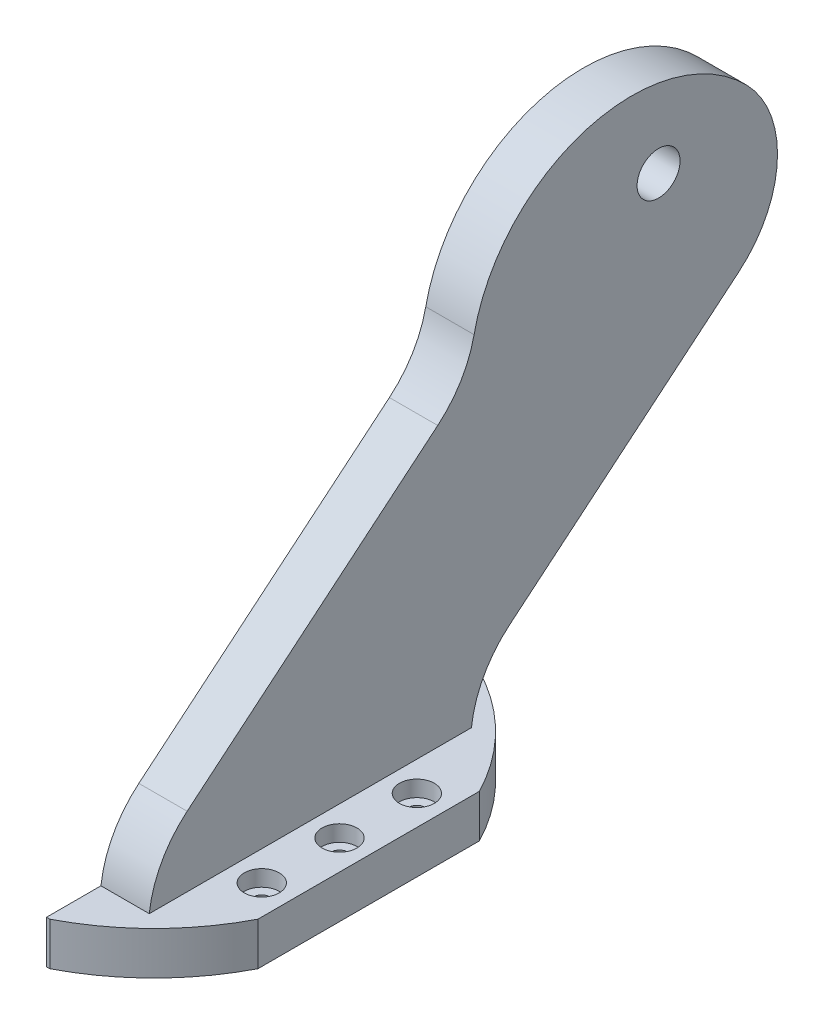
SolidWorks part; units mm, degrees
ref_plane "Alzado" through (0, 0, 0) normal (0, 0, 1) x (1, 0, 0)
ref_plane "Planta" through (0, 0, 0) normal (0, 1, 0) x (1, 0, 0)
ref_plane "Vista lateral" through (0, 0, 0) normal (1, 0, 0) x (0, 0, -1)
sketch "Croquis1" plane through (0, 0, 0) normal (0, 1, 0) x (1, 0, 0)
  line L0 (0, 0) -> (0, 40)
  line L1 (0, 40) -> (20, 40)
  line L2 (20, 40) -> (20, -40)
  line L3 (20, -40) -> (0, -40)
  line L4 (0, -40) -> (0, 0)
extrude "Saliente-Extruir2" add sketch "Croquis1" along normal blind 8
sketch "Croquis3" plane through (0, 8, 0) normal (0, 1, 0) x (1, 0, 0)
  line L0 (20, 0) -> (-20, 0) construction
  line L1 (20, -40) -> (20, 40) construction
  line L3 (0, 40) -> (20, 40)
  line L4 (0, 40) -> (0, -40)
  line L5 (0, -40) -> (20, -40)
  line L6 (20, 40) -> (20, -40)
  circle A0 centre (-20, 0) radius 45
  line M9 (20, -40) -> (20, 40)
  line M10 (20, 40) -> (0, 40)
extrude "Cortar-Extruir1" cut sketch "Croquis3" against normal blind 8 contours A0 M9 M10 | A0 L5 M9
sketch "Croquis4" plane through (0, 0, 0) normal (1, 0, 0) x (0, 0, -1)
  line L0 (0, 0) -> (-30, 0)
  line L1 (40, 0) -> (-40, 0) construction
  line L2 (0, 0) -> (30, 0)
  line L3 (30, 0) -> (30, 5.6325)
  line L4 (-30, 0) -> (-30, 5.6325)
  line L5 (0, 0) -> (0, 80) construction
  line L6 (0, 80) -> (65, 80) construction
  line L8 (65, 95) -> (35, 95) construction
  line L9 (65, 95) -> (90, 95) construction
  line L10 (90, 95) -> (90, 65) construction
  line L11 (79.953, 56.6275) -> (37.1963, 20.9969)
  line L15 (23.8662, 59.8885) -> (-22.8037, 20.9969)
  circle A6 centre (65, 80) radius 4
  arc A7 (81.448, 85.9758) -> (30.6375, 71.1518) centre (60, 65) ccw
  arc A8 (81.448, 85.9758) -> (79.953, 56.6275) centre (67.1493, 71.9919) cw
  arc A9 (-30, 5.6325) -> (-22.8037, 20.9969) centre (-10, 5.6325) cw
  arc A10 (30, 5.6325) -> (37.1963, 20.9969) centre (50, 5.6325) cw
  arc A11 (30.6375, 71.1518) -> (23.8662, 59.8885) centre (11.0625, 75.2529) cw
  dimension "D1" = 20
  dimension "D2" = 20
extrude "Saliente-Extruir3" add sketch "Croquis4" along normal blind 13
ref_plane "Plano1" through (0, 95, 0) normal (0, 1, 0) x (1, 0, 0)
sketch "Croquis5" plane through (0, 95, 0) normal (0, 1, 0) x (1, 0, 0)
  line L0 (20, 0) -> (9, 0) construction
  line L1 (20, -20.6155) -> (20, 20.6155) construction
  line L2 (13, 87.1493) -> (0, 87.1493) construction
  line L3 (9, 87.1493) -> (20, 87.1493)
  line L4 (9, 87.1493) -> (9, -45.8669)
  line L5 (9, -45.8669) -> (20, -45.8669)
  line L6 (20, 87.1493) -> (20, -45.8669)
extrude "Cortar-Extruir2" cut sketch "Croquis5" against normal blind 87
sketch "Croquis7" plane through (0, 8, 0) normal (0, 1, 0) x (1, 0, 0)
  line L0 (20, 0) -> (9, 0.1406) construction
  line L1 (20, -20.6155) -> (20, 20.6155) construction
  line L2 (9, 30.1406) -> (9, -29.8594) construction
  line L3 (14.5, 0.0703) -> (14.5, -28.892) construction
  line L4 (14.5, 0.0703) -> (14.5, 28.892) construction
  arc A1 (0.6155, -40) -> (20, -20.6155) centre (-20, 0) ccw construction
  arc A2 (20, 20.6155) -> (0.6155, 40) centre (-20, 0) ccw construction
  circle A3 centre (14.5, 14.4812) radius 1.5
  circle A4 centre (14.5, 0.0703) radius 1.5
  circle A5 centre (14.5, -14.4109) radius 1.5
extrude "Cortar-Extruir3" cut sketch "Croquis7" against normal blind 87
sketch "Croquis8" plane through (0, 8, 0) normal (0, 1, 0) x (1, 0, 0)
  circle A0 centre (14.5, 14.4812) radius 3.25
  circle A1 centre (14.5, 0.0703) radius 3.25
  circle A2 centre (14.5, -14.4109) radius 3.25
extrude "Cortar-Extruir4" cut sketch "Croquis8" against normal blind 3
